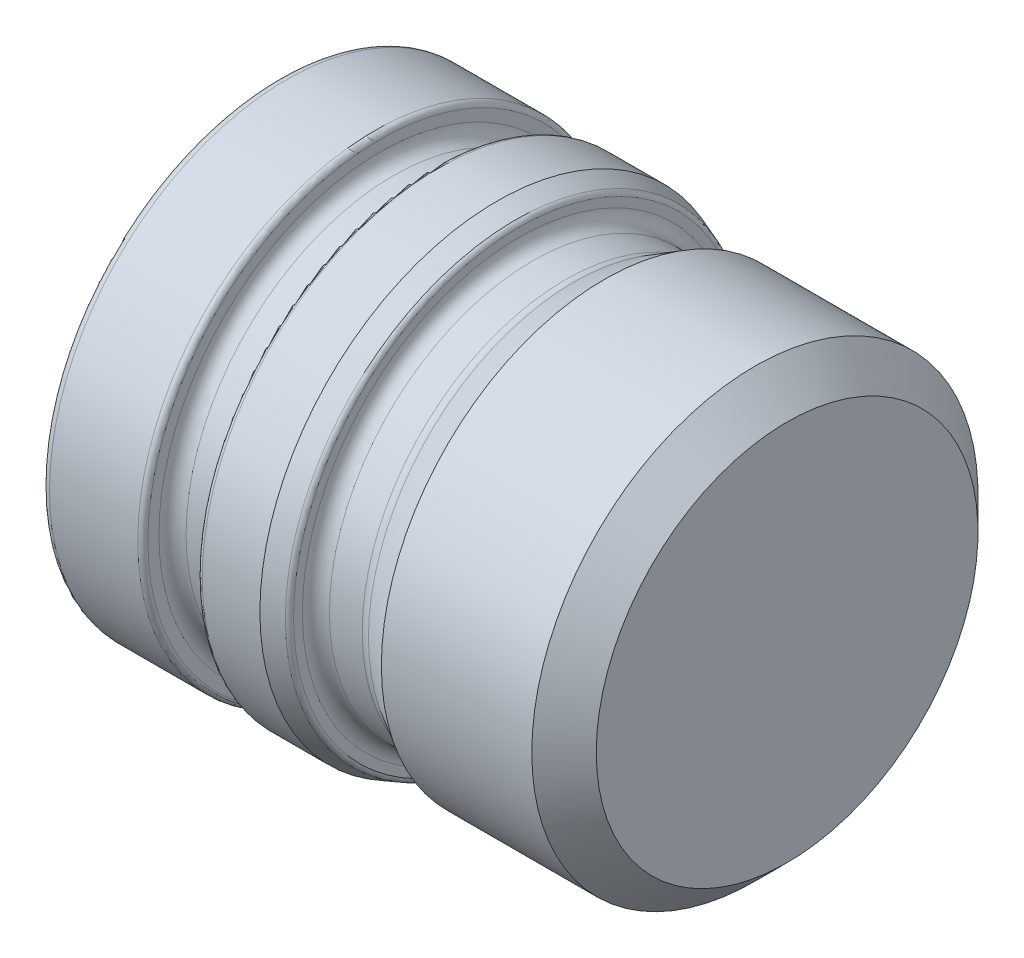
SolidWorks part; units mm, degrees
material "4140 H/T"
ref_plane "Front Plane" through (0, 0, 0) normal (0, 0, 1) x (1, 0, 0)
ref_plane "Top Plane" through (0, 0, 0) normal (0, 1, 0) x (1, 0, 0)
ref_plane "Right Plane" through (0, 0, 0) normal (1, 0, 0) x (0, 0, -1)
sketch "Sketch1" plane through (0, 0, 0) normal (0, 0, 1) x (1, 0, 0)
  line L0 (0, 0) -> (0, 11.25)
  line L1 (0, 11.25) -> (-1.9, 13.15)
  line L2 (-1.9, 13.15) -> (-10.7648, 13.15)
  line L3 (-10.7648, 13.15) -> (-12.5679, 12.109)
  line L4 (-13.0679, 11.975) -> (-15, 11.975)
  line L5 (-15.8, 12.775) -> (-15.8, 13.2918)
  line L6 (-17.1, 13.975) -> (-20.5, 13.975)
  line L7 (-20.8, 13.675) -> (-20.8, 13.025)
  line L8 (-21.6, 12.225) -> (-23.2, 12.225)
  line L9 (-24, 13.025) -> (-24, 13.675)
  line L10 (-24.3, 13.975) -> (-29.5, 13.975)
  line L11 (-30, 13.475) -> (-30, 0)
  line L12 (-30, 0) -> (0, 0)
  line L13 (0, 0) -> (15.3627, 0) construction
  line L14 (-17.1, 13.975) -> (-15.9974, 13.5737)
  arc A0 (-23.2, 12.225) -> (-24, 13.025) centre (-23.2, 13.025) cw
  arc A1 (-20.8, 13.025) -> (-21.6, 12.225) centre (-21.6, 13.025) cw
  arc A2 (-29.5, 13.975) -> (-30, 13.475) centre (-29.5, 13.475) ccw
  arc A3 (-15.9974, 13.5737) -> (-15.8, 13.2918) centre (-16.1, 13.2918) cw
  arc A4 (-20.5, 13.975) -> (-20.8, 13.675) centre (-20.5, 13.675) ccw
  arc A5 (-24, 13.675) -> (-24.3, 13.975) centre (-24.3, 13.675) ccw
  arc A6 (-12.5679, 12.109) -> (-13.0679, 11.975) centre (-13.0679, 12.975) cw
  arc A7 (-15, 11.975) -> (-15.8, 12.775) centre (-15, 12.775) cw
  point P17 (-24, 12.225)
  point P20 (-20.8, 12.225)
  point P32 (-12.8, 11.975)
  dimension "D13" = 0.8
  dimension "D14" = 0.5
  dimension "D15" = 0.3
  dimension "D18" = 0.3
  dimension "D19" = 1
  dimension "D20" = 0.8
  dimension "D1" = 30
  dimension "D2" = 27.95
  dimension "D3" = 24.45
  dimension "D4" = 3.2
  dimension "D5" = 6
  dimension "D6" = 15.8
  dimension "D7" = 26.3
  dimension "D8" = 23.95
  dimension "D9" = 30
  dimension "D10" = 3
  dimension "D11" = 45
  dimension "D12" = 22.5
  dimension "D16" = 1.3
  dimension "D17" = 20
revolve "Revolve1" add sketch "Sketch1" angle 360 about L13
cosmetic thread "Cosmetic Thread1" parameters "D2"=20.6
sketch "Sketch2" plane through (-30, 0, 0) normal (-1, 0, 0) x (0, 0, 1)
  line L1 (-5, 5) -> (5, 5)
  line L2 (-5, 5) -> (-5, -4.75)
  line L3 (-5, -4.75) -> (5, -4.75)
  line L4 (5, 5) -> (5, -4.75)
  dimension "D1" = 10
  dimension "D2" = 9.75
  dimension "D3" = 5
  dimension "D4" = 5
extrude "Cut-Extrude1" cut sketch "Sketch2" against normal blind 10
sketch "Sketch3" plane through (-30, 0, 0) normal (-1, 0, 0) x (0, 0, 1)
  line L0 (0, 0) -> (-5, 5) construction
  line L1 (0, 0) -> (0, 7.9491) construction
  line L2 (0, 0) -> (7.812, 0) construction
  line L3 (5, 5) -> (-5, 5) construction
  circle A0 centre (-3.8, 3.8) radius 1.75
  circle A1 centre (3.8, 3.8) radius 1.75
  circle A2 centre (-3.8, -3.8) radius 1.75
  circle A3 centre (3.8, -3.8) radius 1.75
  dimension "D1" = 3.5
  dimension "D2" = 1.2
extrude "Cut-Extrude2" cut sketch "Sketch3" against normal up to surface (10 mm away) up to face at (-20, 0.125, 0)
chamfer "Chamfer1" distance 0.5 angle 45 8 edges at (-30, 0, 5) (-30, 5, 0) (-30, 0, -5) (-30, -4.75, 0) (-30, 5.0374, -5.0374) (-30, -5.1446, -4.92) (-30, -5.1446, 4.92) (-30, 5.0374, 5.0374)
